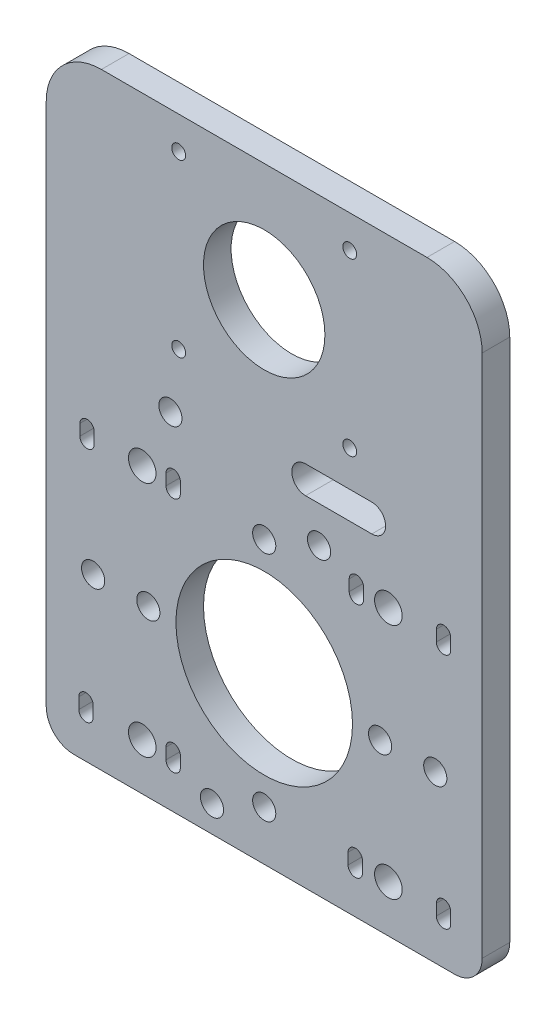
SolidWorks part; units mm, degrees
material "6061 Alloy"
ref_plane "Front Plane" through (0, 0, 0) normal (0, 0, 1) x (1, 0, 0)
ref_plane "Top Plane" through (0, 0, 0) normal (0, 1, 0) x (1, 0, 0)
ref_plane "Right Plane" through (0, 0, 0) normal (1, 0, 0) x (0, 0, -1)
sketch "Sketch1" plane through (0, 0, 0) normal (0, 0, 1) x (1, 0, 0)
  line L0 (-34.5, -0.0124) -> (-24.5, -0.0124) construction
  line L1 (-39.5, 55) -> (39.5, 55)
  line L2 (-39.5, 55) -> (-39.5, -55)
  line L3 (-39.5, -55) -> (39.5, -55)
  line L4 (39.5, 55) -> (39.5, -55)
  line L5 (0, -55) -> (0, 55) construction
  line L6 (-39.5, 0) -> (39.5, 0) construction
  line L7 (-21, -46) -> (21, -46)
  line L8 (-21, -46) -> (-21, -4)
  line L9 (-21, -4) -> (21, -4)
  line L10 (21, -46) -> (21, -4)
  line L11 (0, -4) -> (0, -46) construction
  line L12 (-21, -25) -> (21, -25) construction
  line L13 (-15.5, 18.1) -> (15.5, 18.1)
  line L14 (-15.5, 18.1) -> (-15.5, 49.1)
  line L15 (-15.5, 49.1) -> (15.5, 49.1)
  line L16 (15.5, 18.1) -> (15.5, 49.1)
  line L17 (0, 49.1) -> (0, 18.1) construction
  line L18 (-15.5, 33.6) -> (15.5, 33.6) construction
  line L19 (-24.5, -50) -> (-24.5, -0.0124) construction
  line L20 (-24.5, -0.0124) -> (-34.5, -0.0124) construction
  line L21 (-34.5, -0.0124) -> (-34.5, -50) construction
  line L22 (34.5, -49.9876) -> (24.5, -49.9876) construction
  line L23 (24.5, -49.9876) -> (24.5, 0) construction
  line L24 (24.5, -49.9876) -> (34.5, -49.9876) construction
  line L25 (34.5, -49.9876) -> (34.5, 0) construction
  line L26 (-34.5, -0.0124) -> (-24.5, -0.0124)
  line L27 (-24.5, -50) -> (-24.5, -0.0124)
  line L28 (-24.5, -0.0124) -> (-34.5, -0.0124)
  line L29 (-34.5, -0.0124) -> (-34.5, -50)
  line L30 (34.5, -49.9876) -> (24.5, -49.9876)
  line L31 (24.5, -49.9876) -> (24.5, 0)
  line L32 (24.5, -49.9876) -> (34.5, -49.9876)
  line L33 (34.5, -49.9876) -> (34.5, 0)
  line L34 (7.5, 9.1) -> (19.5, 9.1) construction
  line L35 (7.5, 11.6) -> (19.5, 11.6)
  line L36 (7.5, 6.6) -> (19.5, 6.6)
  circle A0 centre (0, -25) radius 16
  circle A1 centre (0, 33.6) radius 11
  circle A2 centre (21, -25) radius 2.1
  circle A3 centre (-21, -25) radius 2.1
  circle A4 centre (0, -4) radius 2.1
  circle A5 centre (0, -46) radius 2.1
  circle A6 centre (15.5, 49.1) radius 1.25
  circle A7 centre (15.5, 18.1) radius 1.25
  circle A8 centre (-15.5, 18.1) radius 1.25
  circle A9 centre (-15.5, 49.1) radius 1.25
  circle A20 centre (-17, 7.5) radius 2.1
  circle A21 centre (-9.4664, -50.1669) radius 2.1 construction
  circle A22 centre (9.941, 0) radius 2.1 construction
  circle A23 centre (-9.4664, -50.1669) radius 2.1
  circle A24 centre (9.941, 0) radius 2.1
  circle A25 centre (9.941, 0) radius 2.1
  circle A26 centre (31, -25) radius 2.1
  circle A27 centre (-9.4664, -50.1669) radius 2.1
  circle A28 centre (-31, -25) radius 2.1
  arc A29 (7.5, 11.6) -> (7.5, 6.6) centre (7.5, 9.1) ccw
  arc A30 (19.5, 6.6) -> (19.5, 11.6) centre (19.5, 9.1) ccw
  point P0 (0, 0)
  point P30 (13.5, 9.1)
  dimension "D6" = 22
  dimension "D7" = 2.5
  dimension "D10" = 32
  dimension "D11" = 4.2
  dimension "D15" = 17
  dimension "D16" = 20
  dimension "D13" = 2.5
  dimension "D17" = 9
  dimension "D14" = 12
  dimension "D1" = 110
  dimension "D2" = 79
  dimension "D3" = 58.6
  dimension "D4" = 15.5
  dimension "D5" = 15.5
  dimension "D8" = 21
  dimension "D9" = 21
  dimension "D12" = 30
extrude "Boss-Extrude1" add sketch "Sketch1" along normal mid plane 5 contours L4 L1 L2 L3 A9 L15 A6 L16 A7 L13 A8 L14 A5 L7 L8 A3 L9 A4 L10 A2 | A9 L14 A8 L13 A7 L16 A6 L15 A1 | A5 L7 L10 A2 L9 A4 L8 A3 A0
extrude "Cut-Extrude1" cut sketch "Sketch2" against normal through all
sketch "Sketch2" plane through (-158.1663, -561.7516, 2.5) normal (0, 0, 1) x (1, 0, 0)
  line L0 (190.6663, 559.2516) -> (190.6663, 557.2516) construction
  line L1 (191.9663, 559.2516) -> (191.9663, 557.2516)
  line L2 (189.3663, 559.2516) -> (189.3663, 557.2516)
  line L3 (174.8663, 557.2516) -> (174.8663, 559.2516) construction
  line L4 (173.5663, 557.2516) -> (173.5663, 559.2516)
  line L5 (176.1663, 557.2516) -> (176.1663, 559.2516)
  line L6 (158.1663, 538.4833) -> (158.1663, 550.6073) construction
  line L7 (158.1663, 550.6073) -> (132.1663, 536.7516) construction
  line L8 (132.1663, 536.7516) -> (121.1663, 536.7516) construction
  line L9 (141.6663, 557.2516) -> (141.6663, 559.2516) construction
  line L10 (142.9663, 557.2516) -> (142.9663, 559.2516)
  line L11 (140.3663, 557.2516) -> (140.3663, 559.2516)
  line L12 (126.0663, 559.2516) -> (126.0663, 557.2516) construction
  line L13 (124.7663, 559.2516) -> (124.7663, 557.2516)
  line L14 (127.3663, 559.2516) -> (127.3663, 557.2516)
  line L15 (125.8663, 514.2516) -> (125.8663, 516.2516) construction
  line L16 (124.5663, 514.2516) -> (124.5663, 516.2516)
  line L17 (127.1663, 514.2516) -> (127.1663, 516.2516)
  line L18 (141.6663, 516.2516) -> (141.6663, 514.2516) construction
  line L19 (142.9663, 516.2516) -> (142.9663, 514.2516)
  line L20 (140.3663, 516.2516) -> (140.3663, 514.2516)
  line L21 (174.6663, 516.2516) -> (174.6663, 514.2516) construction
  line L22 (173.3663, 516.2516) -> (173.3663, 514.2516)
  line L23 (175.9663, 516.2516) -> (175.9663, 514.2516)
  line L24 (190.6663, 514.2516) -> (190.6663, 516.2516) construction
  line L25 (191.9663, 514.2516) -> (191.9663, 516.2516)
  line L26 (189.3663, 514.2516) -> (189.3663, 516.2516)
  arc A1 (191.9663, 559.2516) -> (189.3663, 559.2516) centre (190.6663, 559.2516) ccw
  arc A2 (189.3663, 557.2516) -> (191.9663, 557.2516) centre (190.6663, 557.2516) ccw
  arc A3 (173.5663, 557.2516) -> (176.1663, 557.2516) centre (174.8663, 557.2516) ccw
  arc A4 (176.1663, 559.2516) -> (173.5663, 559.2516) centre (174.8663, 559.2516) ccw
  arc A8 (142.9663, 557.2516) -> (140.3663, 557.2516) centre (141.6663, 557.2516) cw
  arc A9 (140.3663, 559.2516) -> (142.9663, 559.2516) centre (141.6663, 559.2516) cw
  arc A10 (124.7663, 559.2516) -> (127.3663, 559.2516) centre (126.0663, 559.2516) cw
  arc A11 (127.3663, 557.2516) -> (124.7663, 557.2516) centre (126.0663, 557.2516) cw
  arc A14 (124.5663, 514.2516) -> (127.1663, 514.2516) centre (125.8663, 514.2516) ccw
  arc A15 (127.1663, 516.2516) -> (124.5663, 516.2516) centre (125.8663, 516.2516) ccw
  arc A16 (142.9663, 516.2516) -> (140.3663, 516.2516) centre (141.6663, 516.2516) ccw
  arc A17 (140.3663, 514.2516) -> (142.9663, 514.2516) centre (141.6663, 514.2516) ccw
  arc A18 (173.3663, 516.2516) -> (175.9663, 516.2516) centre (174.6663, 516.2516) cw
  arc A19 (175.9663, 514.2516) -> (173.3663, 514.2516) centre (174.6663, 514.2516) cw
  arc A20 (191.9663, 514.2516) -> (189.3663, 514.2516) centre (190.6663, 514.2516) cw
  arc A21 (189.3663, 516.2516) -> (191.9663, 516.2516) centre (190.6663, 516.2516) cw
  circle A23 centre (136.0663, 558.2516) radius 2.5
  circle A24 centre (180.6663, 558.2516) radius 2.5
  circle A25 centre (136.0663, 515.2516) radius 2.5
  circle A26 centre (180.6663, 515.2516) radius 2.5
  point P7 (190.6663, 558.2516)
  point P12 (174.8663, 558.2516)
  point P36 (141.6663, 558.2516)
  point P43 (126.0663, 558.2516)
  point P54 (125.8663, 515.2516)
  point P61 (141.6663, 515.2516)
  point P68 (174.6663, 515.2516)
  point P75 (190.6663, 515.2516)
  dimension "D1" = 10
  dimension "D2" = 10
  dimension "D3" = 5
  dimension "D4" = 1.3
  dimension "D5" = 1.3
fillet "Fillet1" radius 10 2 edges at (-39.5, 55, 0) (39.5, 55, 0)
fillet "Fillet2" radius 5 2 edges at (39.5, -55, 0) (-39.5, -55, 0)
extrude "Cut-Extrude2" cut sketch "Sketch3" against normal blind 10
sketch "Sketch3" plane through (-41.9145, -496.2571, 2.5) normal (0, 0, 1) x (0.9503, 0.3112, 0)
  line L0 (191.1288, 400.7207) -> (191.1288, 398.7207) construction
  line L1 (192.2288, 400.7207) -> (192.2288, 398.7207)
  line L2 (190.0288, 400.7207) -> (190.0288, 398.7207)
  line L3 (175.1288, 398.7207) -> (175.1288, 400.7207) construction
  line L4 (174.0288, 398.7207) -> (174.0288, 400.7207)
  line L5 (176.2288, 398.7207) -> (176.2288, 400.7207)
  line L6 (158.6288, 538.4833) -> (158.6288, 392.0764) construction
  line L7 (158.6288, 392.0764) -> (132.6288, 378.2207) construction
  line L8 (132.6288, 378.2207) -> (121.6288, 378.2207) construction
  line L9 (142.1288, 398.7207) -> (142.1288, 400.7207) construction
  line L10 (143.2288, 398.7207) -> (143.2288, 400.7207)
  line L11 (141.0288, 398.7207) -> (141.0288, 400.7207)
  line L12 (126.1288, 400.7207) -> (126.1288, 398.7207) construction
  line L13 (125.0288, 400.7207) -> (125.0288, 398.7207)
  line L14 (127.2288, 400.7207) -> (127.2288, 398.7207)
  line L15 (126.1288, 355.7207) -> (126.1288, 357.7207) construction
  line L16 (125.0288, 355.7207) -> (125.0288, 357.7207)
  line L17 (127.2288, 355.7207) -> (127.2288, 357.7207)
  line L18 (142.1288, 357.7207) -> (142.1288, 355.7207) construction
  line L19 (143.2288, 357.7207) -> (143.2288, 355.7207)
  line L20 (141.0288, 357.7207) -> (141.0288, 355.7207)
  line L21 (175.1288, 357.7207) -> (175.1288, 355.7207) construction
  line L22 (174.0288, 357.7207) -> (174.0288, 355.7207)
  line L23 (176.2288, 357.7207) -> (176.2288, 355.7207)
  line L24 (191.1288, 355.7207) -> (191.1288, 357.7207) construction
  line L25 (192.2288, 355.7207) -> (192.2288, 357.7207)
  line L26 (190.0288, 355.7207) -> (190.0288, 357.7207)
  arc A1 (192.2288, 400.7207) -> (190.0288, 400.7207) centre (191.1288, 400.7207) ccw
  arc A2 (190.0288, 398.7207) -> (192.2288, 398.7207) centre (191.1288, 398.7207) ccw
  arc A3 (174.0288, 398.7207) -> (176.2288, 398.7207) centre (175.1288, 398.7207) ccw
  arc A4 (176.2288, 400.7207) -> (174.0288, 400.7207) centre (175.1288, 400.7207) ccw
  arc A8 (143.2288, 398.7207) -> (141.0288, 398.7207) centre (142.1288, 398.7207) cw
  arc A9 (141.0288, 400.7207) -> (143.2288, 400.7207) centre (142.1288, 400.7207) cw
  arc A10 (125.0288, 400.7207) -> (127.2288, 400.7207) centre (126.1288, 400.7207) cw
  arc A11 (127.2288, 398.7207) -> (125.0288, 398.7207) centre (126.1288, 398.7207) cw
  arc A14 (125.0288, 355.7207) -> (127.2288, 355.7207) centre (126.1288, 355.7207) ccw
  arc A15 (127.2288, 357.7207) -> (125.0288, 357.7207) centre (126.1288, 357.7207) ccw
  arc A16 (143.2288, 357.7207) -> (141.0288, 357.7207) centre (142.1288, 357.7207) ccw
  arc A17 (141.0288, 355.7207) -> (143.2288, 355.7207) centre (142.1288, 355.7207) ccw
  arc A18 (174.0288, 357.7207) -> (176.2288, 357.7207) centre (175.1288, 357.7207) cw
  arc A19 (176.2288, 355.7207) -> (174.0288, 355.7207) centre (175.1288, 355.7207) cw
  arc A20 (192.2288, 355.7207) -> (190.0288, 355.7207) centre (191.1288, 355.7207) cw
  arc A21 (190.0288, 357.7207) -> (192.2288, 357.7207) centre (191.1288, 357.7207) cw
  circle A23 centre (131.1288, 399.7207) radius 2.5
  circle A24 centre (186.1288, 399.7207) radius 2.5
  circle A25 centre (131.1288, 356.7207) radius 2.5
  circle A26 centre (186.1288, 356.7207) radius 2.5
  point P7 (191.1288, 399.7207)
  point P12 (175.1288, 399.7207)
  point P36 (142.1288, 399.7207)
  point P43 (126.1288, 399.7207)
  point P54 (126.1288, 356.7207)
  point P61 (142.1288, 356.7207)
  point P68 (175.1288, 356.7207)
  point P75 (191.1288, 356.7207)
